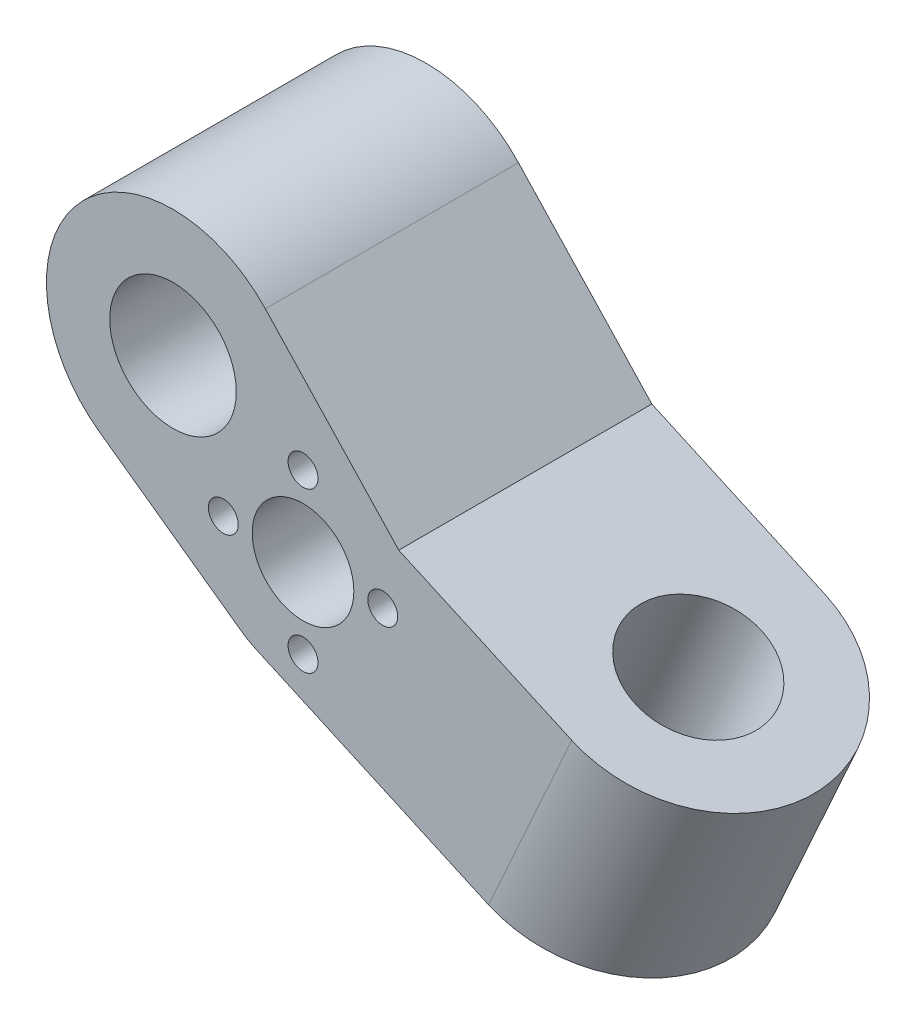
SolidWorks part; units mm, degrees
ref_plane "Front Plane" through (0, 0, 0) normal (0, 0, 1) x (1, 0, 0)
ref_plane "Top Plane" through (0, 0, 0) normal (0, 1, 0) x (1, 0, 0)
ref_plane "Right Plane" through (0, 0, 0) normal (1, 0, 0) x (0, 0, -1)
sketch "Sketch1" plane through (0, 0, 0) normal (0, 0, 1) x (1, 0, 0)
  line L0 (-65.3961, -44.1613) -> (-78.7821, -29.8796)
  line L1 (-95.4426, -48.89) -> (-81.4046, -58.9432)
  line L2 (-65.3961, -44.1613) -> (-36.4595, -57.2276)
  line L3 (-36.4595, -57.2276) -> (-44.8029, -75.705)
  line L4 (-44.8029, -75.705) -> (-79.5269, -60.0253)
  line L5 (-71.7994, -34.0572) -> (-95.4118, -23.3951) construction
  circle A0 centre (-88.0482, -38.5646) radius 6.35 construction
  circle A1 centre (-75, -50) radius 11 construction
  circle A2 centre (-88.0482, -38.5646) radius 6.35
  arc A3 (-83.2726, -42.7499) -> (-79.5269, -60.0253) centre (-75, -50) ccw
  arc A4 (-95.4426, -48.89) -> (-78.7821, -29.8796) centre (-88.0482, -38.5646) cw
  circle A5 centre (-75, -58) radius 1.5 construction
  circle A6 centre (-83, -50) radius 1.5 construction
  circle A7 centre (-67, -50) radius 1.5 construction
  circle A8 centre (-75, -42) radius 1.5 construction
  circle A9 centre (-75, -58) radius 1.5
  circle A10 centre (-83, -50) radius 1.5
  circle A11 centre (-67, -50) radius 1.5
  circle A12 centre (-75, -42) radius 1.5
  circle A13 centre (-75, -50) radius 5.1 construction
  circle A14 centre (-75, -50) radius 5.1
  point P25 (0, 0)
  point P31 (0, 0)
  dimension "D1" = 12.7
  dimension "D2" = 38.1
  dimension "D3" = 31.75
extrude "Boss-Extrude1" add sketch "Sketch1" along normal blind 25.4
sketch "Sketch2" plane through (-27.6396, -61.2103, 0) normal (0.4115, 0.9114, 0) x (0.9114, -0.4115, 0)
  line L0 (-41.4274, -25.4) -> (-9.6774, -25.4) construction
  line L1 (-9.6774, -25.4) -> (-9.6774, 0) construction
  line L2 (-41.4274, 0) -> (-9.6774, 0) construction
  line L3 (-22.3774, -25.4) -> (-9.6774, -25.4)
  line L4 (-9.6774, -25.4) -> (-9.6774, 0)
  line L5 (-9.6774, 0) -> (-22.3774, 0)
  circle A0 centre (-22.3774, -12.7) radius 6.35
  arc A1 (-22.3774, 0) -> (-22.3774, -25.4) centre (-22.3774, -12.7) cw
  line M3 (-9.6774, 0) -> (-41.4274, 0)
  line M5 (-41.4274, -25.4) -> (-9.6774, -25.4)
  line M6 (-9.6774, -25.4) -> (-9.6774, 0)
  dimension "D3" = 12.7
  dimension "D1" = 12.7
  dimension "D2" = 12.7
extrude "Cut-Extrude1" cut sketch "Sketch2" against normal up to surface (20.2738 mm away) contours A1 L4 M3 | A1 M6 M5 | A0 up to face at (-62.1649, -67.8651, 12.7)
